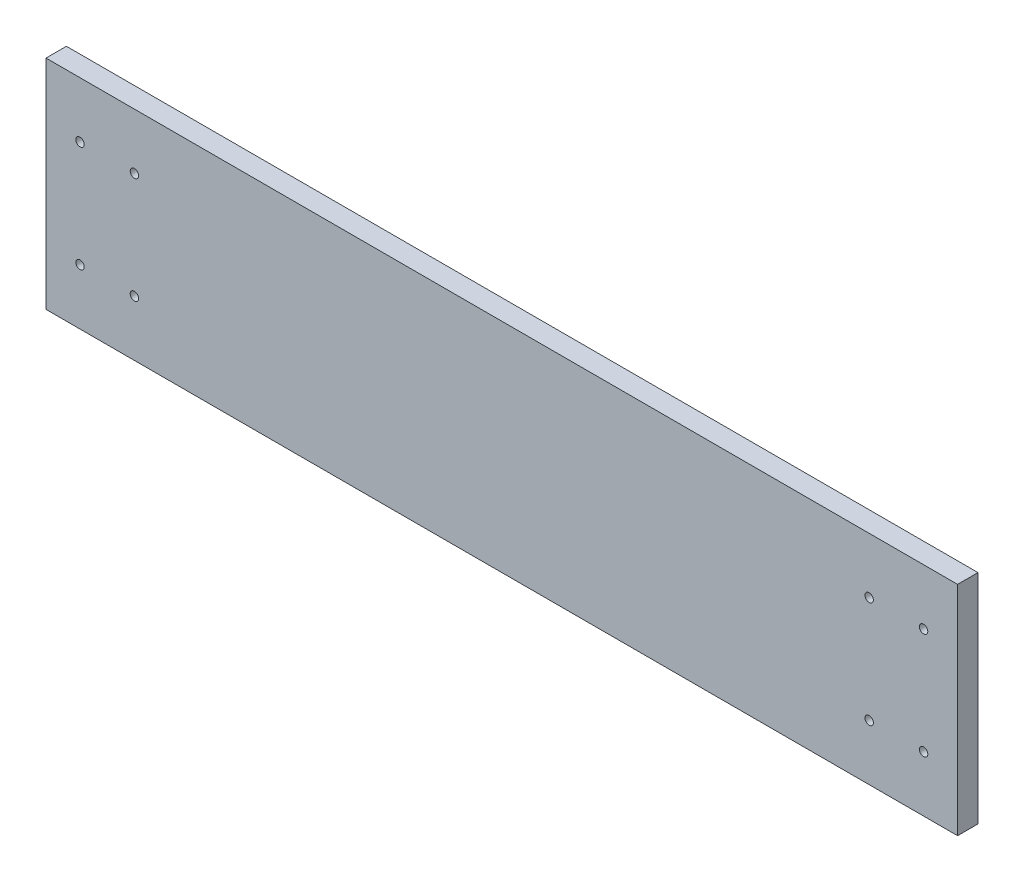
SolidWorks part; units mm, degrees
material "Balsa"
ref_plane "Front Plane" through (0, 0, 0) normal (0, 0, 1) x (1, 0, 0)
ref_plane "Top Plane" through (0, 0, 0) normal (0, 1, 0) x (1, 0, 0)
ref_plane "Right Plane" through (0, 0, 0) normal (1, 0, 0) x (0, 0, -1)
sketch "Sketch1" plane through (0, 0, 0) normal (0, 0, 1) x (1, 0, 0)
  line L1 (0, 0) -> (850.9, 0)
  line L2 (0, 0) -> (0, 203.2)
  line L3 (0, 203.2) -> (850.9, 203.2)
  line L4 (850.9, 0) -> (850.9, 203.2)
  dimension "D1" = 850.9
  dimension "D2" = 203.2
extrude "Boss-Extrude1" add sketch "Sketch1" along normal blind 19.05
sketch "Esquisse1" plane through (0, 0, 0) normal (0, 0, -1) x (-1, 0, 0)
  line L0 (-850.9, 203.2) -> (0, 203.2) construction
  line L1 (-850.9, 0) -> (-850.9, 203.2) construction
  line L2 (0, 203.2) -> (0, 0) construction
  circle A0 centre (-819.15, 151.2) radius 3.937
  circle A1 centre (-768.35, 151.2) radius 3.937
  circle A2 centre (-768.35, 52) radius 3.937
  circle A3 centre (-819.15, 52) radius 3.937
  circle A4 centre (-82.55, 151.2) radius 3.937
  circle A5 centre (-31.75, 151.2) radius 3.937
  circle A6 centre (-31.75, 52) radius 3.937
  circle A7 centre (-82.55, 52) radius 3.937
  dimension "D1" = 7.874
  dimension "D2" = 50.8
  dimension "D3" = 50.8
  dimension "D4" = 99.2
  dimension "D5" = 99.2
  dimension "D6" = 52
  dimension "D7" = 31.75
  dimension "D8" = 50.8
  dimension "D9" = 111.4508
  dimension "D10" = 31.75
  dimension "D11" = 50.8
  dimension "D12" = 50.8
  dimension "D13" = 111.4508
  dimension "D14" = 111.4508
  dimension "D15" = 99.2
  dimension "D16" = 52
extrude "Enlèv. mat.-Extru.1" cut sketch "Esquisse1" against normal through all
